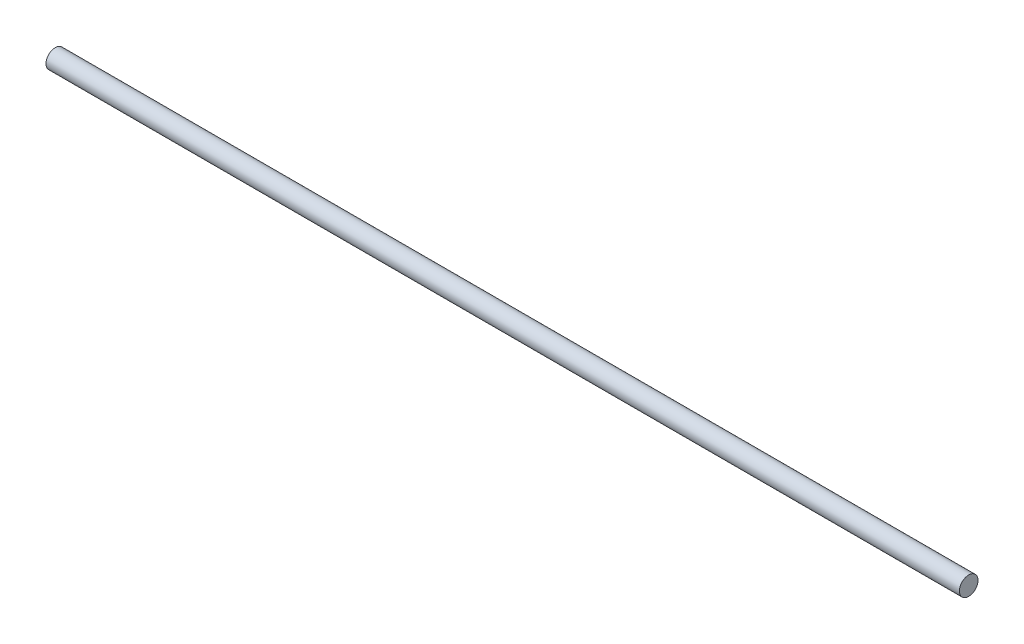
SolidWorks part; units mm, degrees
ref_plane "Front Plane" through (0, 0, 0) normal (1, 0, 0) x (0, 1, 0)
ref_plane "Top Plane" through (0, 0, 0) normal (0, 0, 1) x (0, 1, 0)
ref_plane "Right Plane" through (0, 0, 0) normal (0, 1, 0) x (-1, 0, 0)
sketch "Sketch1" plane through (0, 0, 0) normal (1, 0, 0) x (0, 1, 0)
  circle A0 centre (0, 0) radius 1.985
  dimension "D1" = 3.97
extrude "Boss-Extrude1" add sketch "Sketch1" along normal mid plane 195 contours A0
